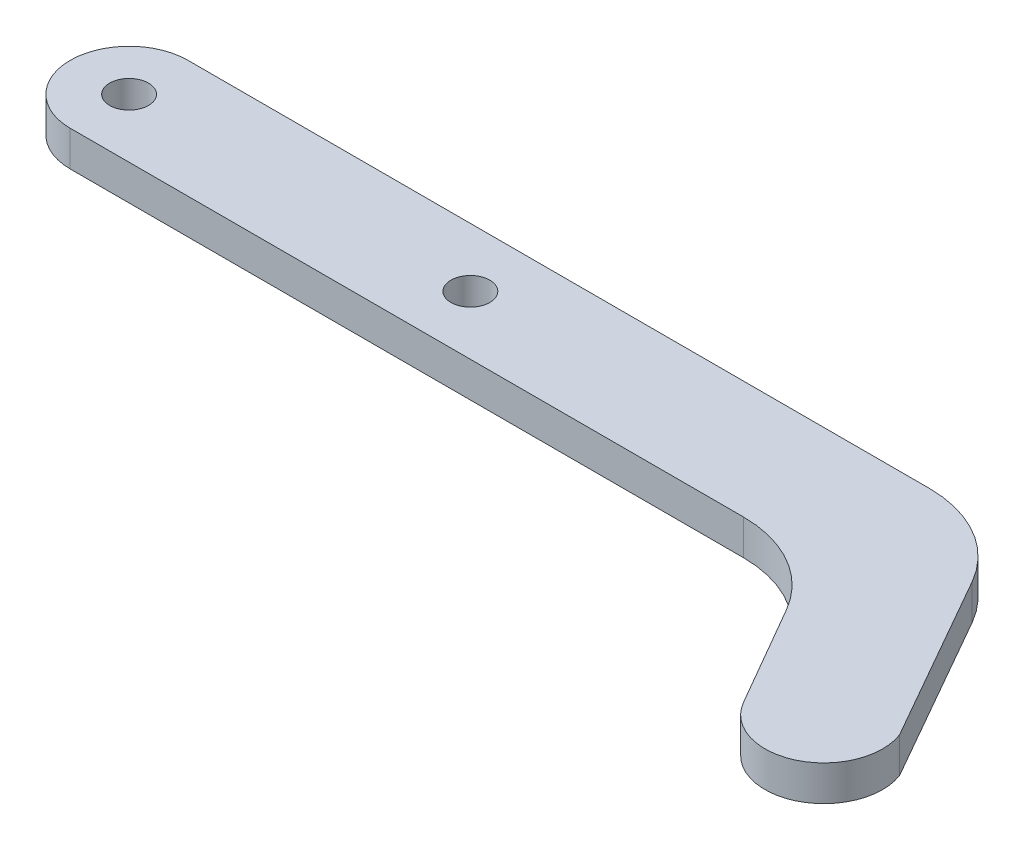
SolidWorks part; units mm, degrees
ref_plane "前视基准面" through (0, 0, 0) normal (0, 0, 1) x (1, 0, 0)
ref_plane "上视基准面" through (0, 0, 0) normal (0, 1, 0) x (1, 0, 0)
ref_plane "右视基准面" through (0, 0, 0) normal (1, 0, 0) x (0, 0, -1)
sketch "草图1" plane through (0, 0, 0) normal (0, 1, 0) x (1, 0, 0)
  line L0 (0, 0) -> (57.2, 0)
  line L1 (65.8603, -5) -> (70.8561, -13.653)
  line L2 (0, 10) -> (63, 10)
  line L3 (79.8707, -9.405) -> (71.6879, 4.9518)
  arc A0 (0, 0) -> (0, 10) centre (0, 5) cw
  arc A1 (70.8561, -13.653) -> (79.8707, -9.405) centre (75.1862, -11.153) ccw
  circle A2 centre (0, 5) radius 1.65
  circle A6 centre (29, 5) radius 1.65
  arc A7 (71.6879, 4.9518) -> (63, 10) centre (63, 0) ccw
  arc A8 (57.2, 0) -> (65.8603, -5) centre (57.2, -10) cw
  dimension "D1" = 10
  dimension "D2" = 10
extrude "凸台-拉伸1" add sketch "草图1" along normal blind 3
